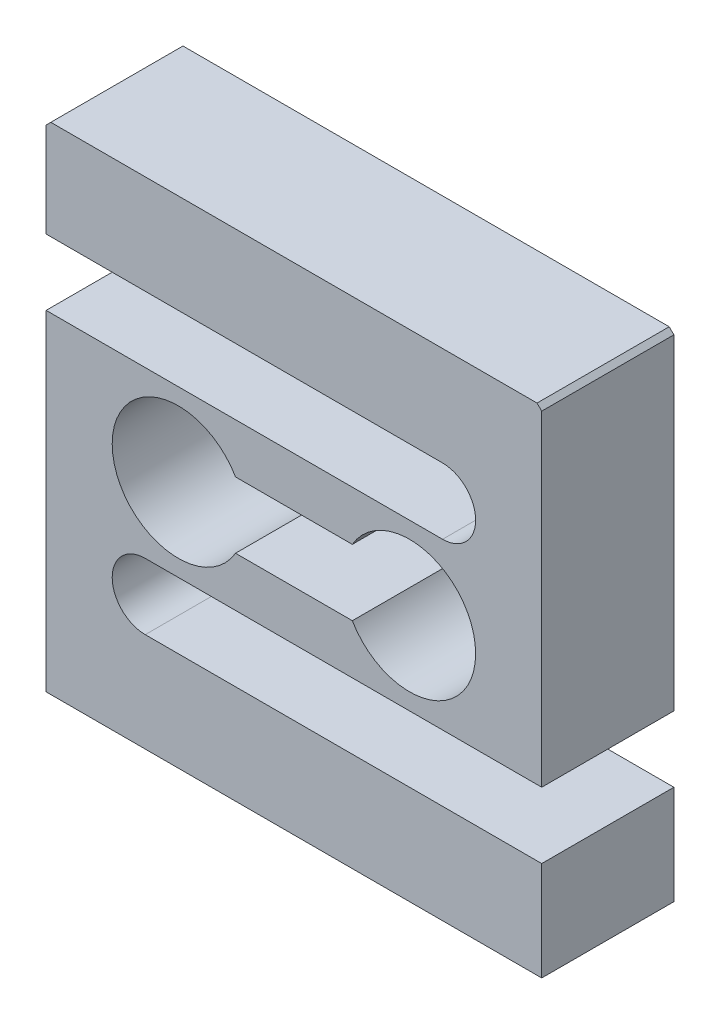
SolidWorks part; units mm, degrees
material "Alliage 1060"
ref_plane "Plan de face" through (0, 0, 0) normal (0, 0, 1) x (1, 0, 0)
ref_plane "Plan de dessus" through (0, 0, 0) normal (0, 1, 0) x (1, 0, 0)
ref_plane "Plan de droite" through (0, 0, 0) normal (1, 0, 0) x (0, 0, -1)
sketch "Esquisse1" plane through (0, 0, 0) normal (0, 0, 1) x (1, 0, 0)
  line L0 (0, 50) -> (0, 0)
  line L1 (0, 0) -> (75, 0)
  line L2 (75, 0) -> (75, 15)
  line L3 (75, 15) -> (15, 15)
  line L4 (15, 25) -> (75, 25)
  line L5 (75, 25) -> (75, 74.2929)
  line L6 (75, 74.2929) -> (74.2929, 75)
  line L7 (74.2929, 75) -> (0.7071, 75)
  line L8 (0.7071, 75) -> (0, 74.2929)
  line L9 (0, 74.2929) -> (0, 60)
  line L10 (0, 60) -> (60, 60)
  line L11 (60, 50) -> (0, 50)
  line L12 (32.7203, 42.5) -> (45.3997, 42.5)
  line L13 (45.3997, 32.5) -> (32.7203, 32.5)
  line L14 (-31.9193, 37.5) -> (114.3913, 37.5) construction
  line L15 (32.7203, 42.5) -> (32.7203, 32.5) construction
  line L16 (45.3997, 42.5) -> (45.3997, 32.5) construction
  arc A0 (15, 15) -> (15, 25) centre (15, 20) cw
  arc A1 (60, 60) -> (60, 50) centre (60, 55) cw
  arc A2 (32.7203, 32.5) -> (32.7203, 42.5) centre (24.06, 37.5) cw
  arc A3 (45.3997, 42.5) -> (45.3997, 32.5) centre (54.06, 37.5) cw
  dimension "D9" = 5
  dimension "D10" = 5
  dimension "D12" = 10
  dimension "D13" = 10
  dimension "D1" = 75
  dimension "D2" = 75
  dimension "D3" = 135
  dimension "D4" = 1
  dimension "D5" = 1
  dimension "D6" = 15
  dimension "D7" = 60
  dimension "D8" = 60
  dimension "D11" = 15
  dimension "D14" = 37.5
  dimension "D15" = 30
  dimension "D16" = 10
  dimension "D17" = 24.06
extrude "Boss.-Extru.1" add sketch "Esquisse1" along normal blind 20 contours L5 L6 L7 L8 L9 L10 A1 L11 L0 L1 L2 L3 A0 L4
sketch "Esquisse2" plane through (0, 0, 0) normal (0, 0, 1) x (1, 0, 0)
  line L1 (74.2929, 75) -> (0.7071, 75) construction
  line L2 (65, 67.6908) -> (65, 7.2664) construction
  line L3 (10, 71.6316) -> (10, 7.2664) construction
  line L12 (28.6603, 42.5) -> (46.3397, 42.5)
  line L13 (46.3397, 32.5) -> (28.6603, 32.5)
  line L14 (-35.9793, 37.5) -> (110.3313, 37.5) construction
  line L15 (28.6603, 42.5) -> (28.6603, 32.5) construction
  line L16 (46.3397, 42.5) -> (46.3397, 32.5) construction
  arc A0 (60, 50) -> (60, 60) centre (60, 55) ccw construction
  arc A1 (15, 25) -> (15, 15) centre (15, 20) ccw construction
  arc A2 (28.6603, 32.5) -> (28.6603, 42.5) centre (20, 37.5) cw
  arc A3 (46.3397, 42.5) -> (46.3397, 32.5) centre (55, 37.5) cw
  dimension "D12" = 10
  dimension "D13" = 10
  dimension "D4" = 37.5
  dimension "D5" = 10
extrude "Enlèv. mat.-Extru.3" cut sketch "Esquisse2" along normal through all contours L12 A3 L13 A2
